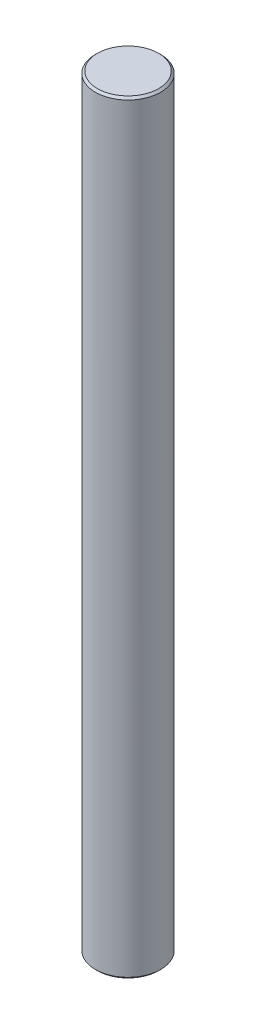
SolidWorks part; units mm, degrees
material "Plain Carbon Steel"
ref_plane "Front Plane" through (0, 0, 0) normal (0, 0, 1) x (1, 0, 0)
ref_plane "Top Plane" through (0, 0, 0) normal (0, 1, 0) x (1, 0, 0)
ref_plane "Right Plane" through (0, 0, 0) normal (1, 0, 0) x (0, 0, -1)
sketch "Sketch1" plane through (0, 0, 0) normal (0, 1, 0) x (1, 0, 0)
  circle A0 centre (0, 0) radius 3.9688
  dimension "D1" = 7.9375
extrude "Boss-Extrude1" add sketch "Sketch1" along normal mid plane 92.71
chamfer "Chamfer1" distance 0.254 angle 45 2 edges at (0, -46.355, 3.9688) (0, 46.355, 3.9688)
